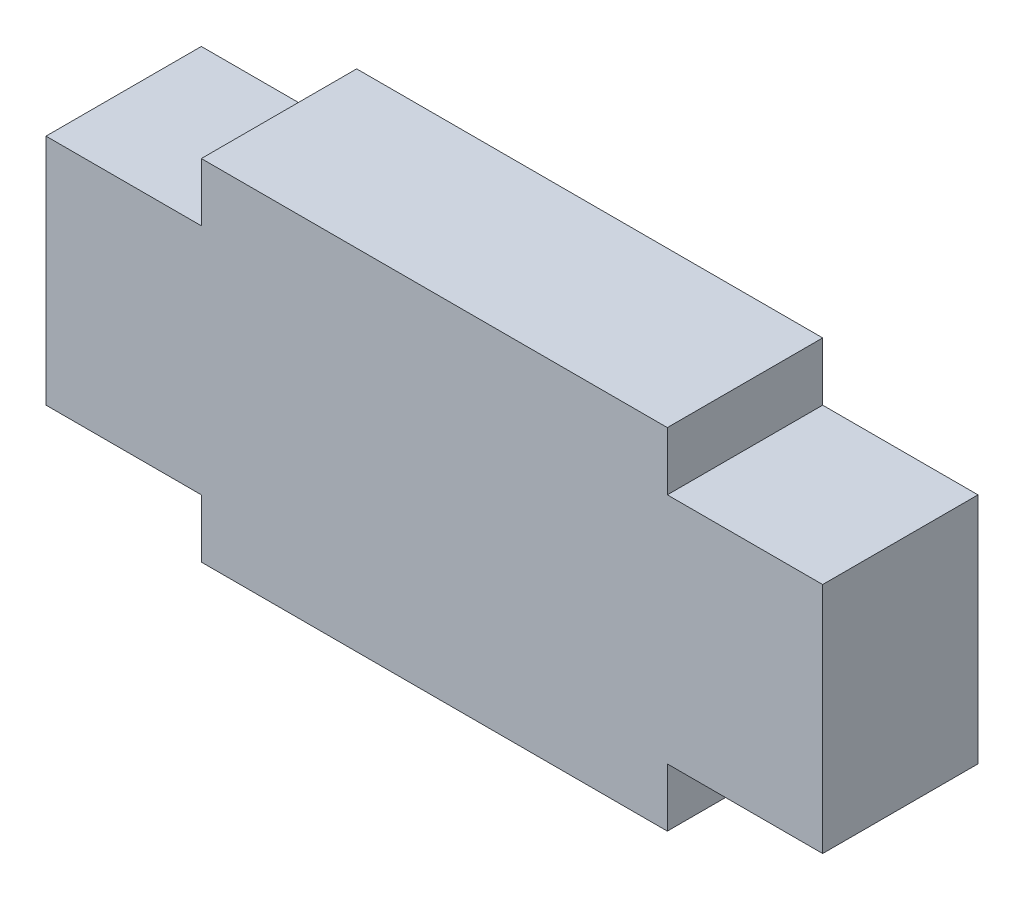
SolidWorks part; units mm, degrees
ref_plane "Спереди" through (0, 0, 0) normal (0, 0, 1) x (1, 0, 0)
ref_plane "Сверху" through (0, 0, 0) normal (0, 1, 0) x (1, 0, 0)
ref_plane "Справа" through (0, 0, 0) normal (1, 0, 0) x (0, 0, -1)
sketch "Эскиз1" plane through (0, 0, 0) normal (0, 0, 1) x (1, 0, 0)
  line L0 (0, 0) -> (0, 6)
  line L1 (0, 6) -> (4, 6)
  line L2 (4, 6) -> (4, 7.5)
  line L3 (4, 7.5) -> (16, 7.5)
  line L4 (16, 7.5) -> (16, 6)
  line L5 (16, 6) -> (20, 6)
  line L6 (20, 6) -> (20, 0)
  line L7 (20, 0) -> (16, 0)
  line L8 (16, 0) -> (16, -1.5)
  line L9 (16, -1.5) -> (4, -1.5)
  line L10 (4, -1.5) -> (4, 0)
  line L11 (4, 0) -> (0, 0)
  dimension "D1" = 20
  dimension "D2" = 4
  dimension "D3" = 6
  dimension "D4" = 9
extrude "Бобышка-Вытянуть1" add sketch "Эскиз1" along normal blind 4
